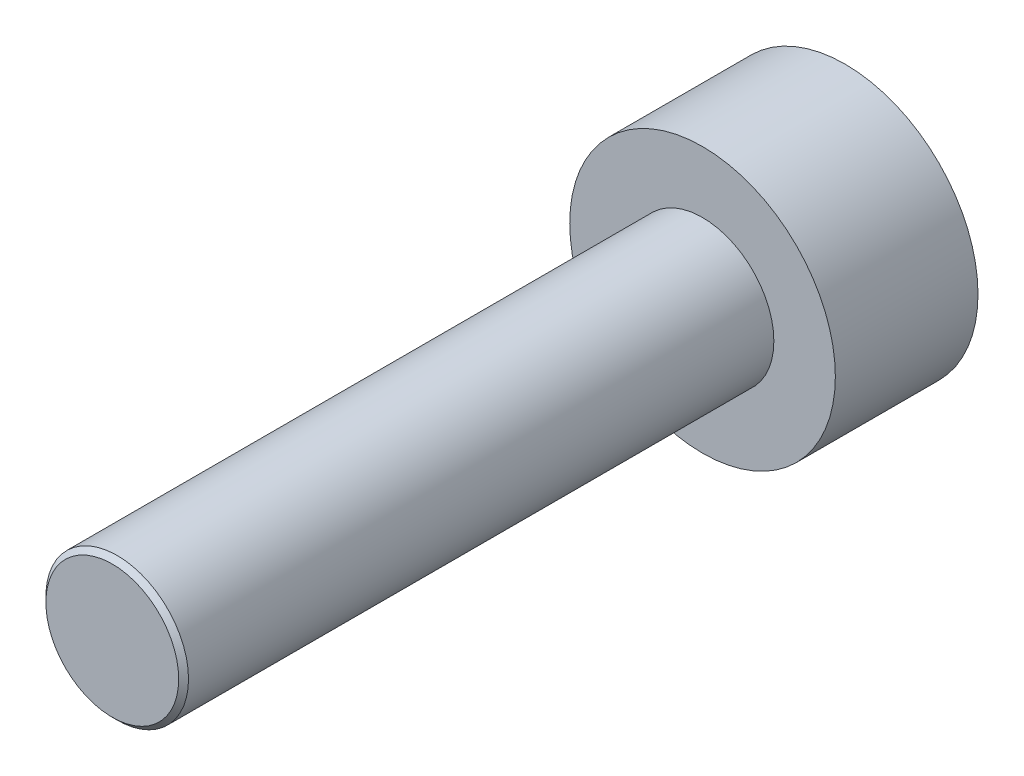
SolidWorks part; units mm, degrees
ref_plane "Ebene vorne" through (0, 0, 0) normal (0, 0, 1) x (1, 0, 0)
ref_plane "Ebene oben" through (0, 0, 0) normal (0, 1, 0) x (1, 0, 0)
ref_plane "Ebene rechts" through (0, 0, 0) normal (1, 0, 0) x (0, 0, -1)
sketch "Skizze1" plane through (0, 0, 0) normal (0, 0, 1) x (1, 0, 0)
  circle A0 centre (0, 0) radius 2.7
  dimension "D1" = 5.4
extrude "Aufsatz-Linear austragen2" add sketch "Skizze1" along normal blind 2.9
sketch "Skizze3" plane through (0, 0, 2.9) normal (0, 0, 1) x (1, 0, 0)
  circle A0 centre (0, 0) radius 1.45
  dimension "D1" = 2.9
extrude "Aufsatz-Linear austragen3" add sketch "Skizze3" along normal blind 12
cosmetic thread "Gewindedarstellung3" parameters "D2"=2.755
chamfer "Fase1" distance 0.1 angle 45 1 edges at (1.45, 0, 14.9)
